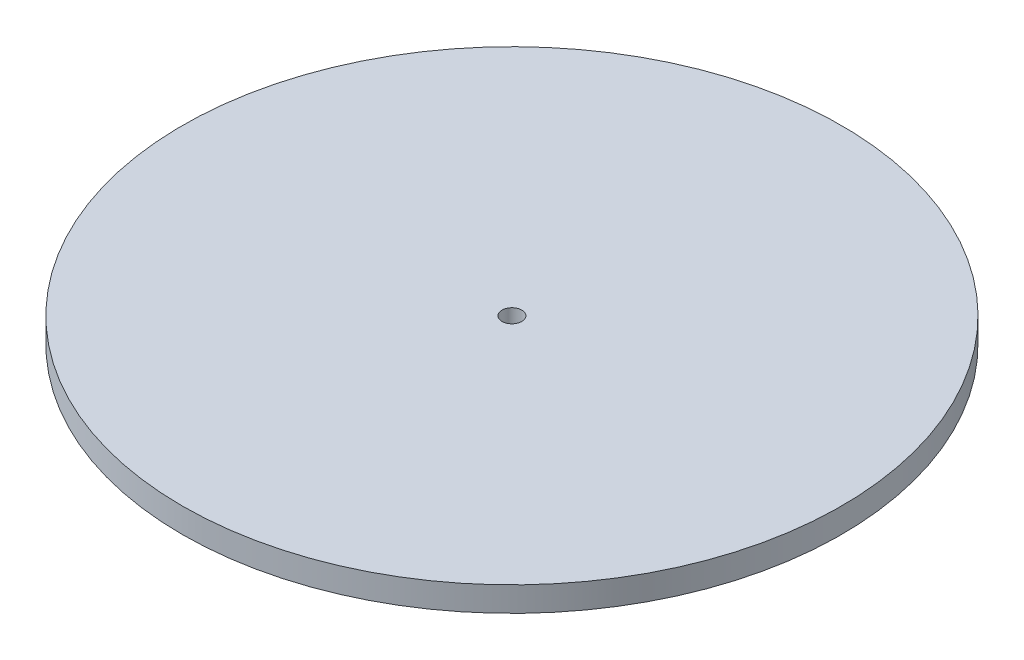
SolidWorks part; units mm, degrees
ref_plane "Front Plane" through (0, 0, 0) normal (0, 0, 1) x (1, 0, 0)
ref_plane "Top Plane" through (0, 0, 0) normal (0, 1, 0) x (1, 0, 0)
ref_plane "Right Plane" through (0, 0, 0) normal (1, 0, 0) x (0, 0, -1)
sketch "Sketch3" plane through (0, 0, 0) normal (0, 0, 1) x (1, 0, 0)
  line L0 (37, 11.9735) -> (37, 15.9735) construction
  line L1 (37, 15.9735) -> (0, 15.9735) construction
  line L2 (0, 15.9735) -> (0, 0) construction
  line L4 (1.2, 15.9735) -> (1.2, 10.9735)
  line L5 (1.2, 10.9735) -> (0, 10.9735)
  line L6 (0, 10.9735) -> (0, 0)
  line L7 (37, 11.9735) -> (40, 11.9735) construction
  line L8 (40, 11.9735) -> (40, 15.9735) construction
  line L9 (40, 15.9735) -> (1.2, 15.9735)
  line L10 (37, 11.9735) -> (37, 12.9735)
  line L11 (37, 12.9735) -> (40, 12.9735)
  line L12 (40, 12.9735) -> (40, 15.9735)
  spline S0 degree 8 poles (-3.7, 0.2392) (1.8411, -0.4394) (7.3823, -0.2196) (12.9234, 2.5888) (18.4645, 4.1277) (24.0057, 6.8471) (29.5468, 8.8782) (35.0879, 11.2551) (40.6291, 13.4164) knots 0 0 0 0 0 0 0 0 0 1 1 1 1 1 1 1 1 1 construction
  spline S1 degree 8 poles (0, 0) (4.625, -0.0008) (9.25, 0.8953) (13.875, 2.7346) (18.5, 4.3795) (23.125, 6.3558) (27.75, 8.21) (32.375, 10.112) (37, 11.9735) knots 0.083467 0.083467 0.083467 0.083467 0.083467 0.083467 0.083467 0.083467 0.083467 0.918133 0.918133 0.918133 0.918133 0.918133 0.918133 0.918133 0.918133 0.918133
  dimension "D1" = 3
  dimension "D2" = 1.2
  dimension "D3" = 5
  dimension "D4" = 3
  dimension "D5" = 40
  dimension "D6" = 11.9735
  dimension "D7" = 37
  dimension "D8" = 4
revolve "Revolve4" add sketch "Sketch3" angle 360 about L2
sketch "Sketch5" plane through (0, 15.9735, 0) normal (0, 1, 0) x (1, 0, 0)
  circle A0 centre (0, 0) radius 1.2
  circle A2 centre (0, 0) radius 1.2 construction
extrude "Cut-Extrude1" cut sketch "Sketch5" against normal through all
